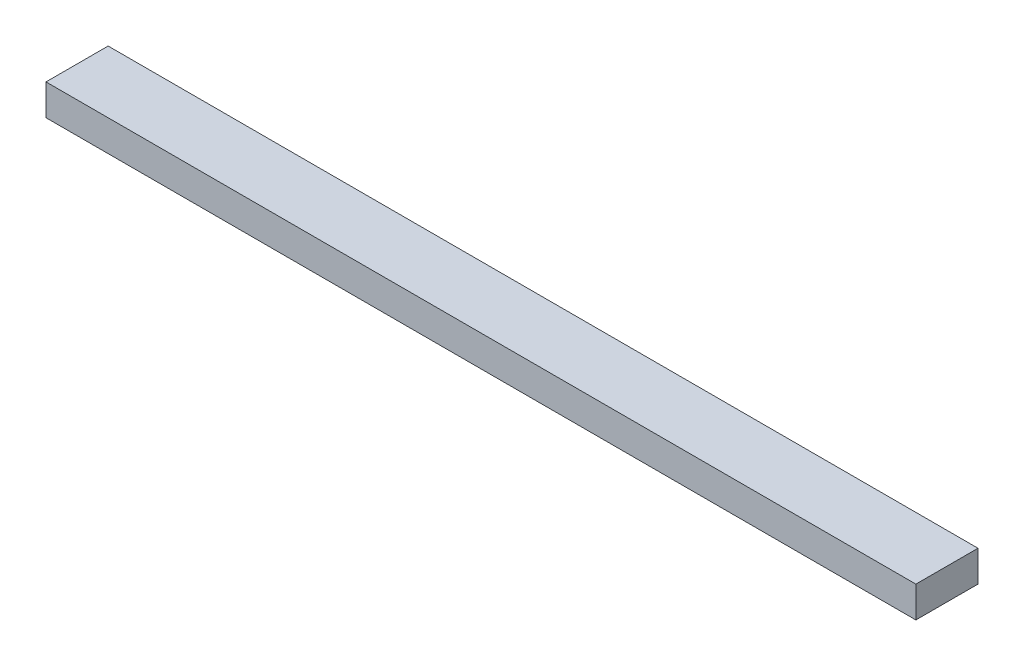
SolidWorks part; units mm, degrees
ref_plane "Front" through (0, 0, 0) normal (0, 0, 1) x (1, 0, 0)
ref_plane "Top" through (0, 0, 0) normal (0, 1, 0) x (1, 0, 0)
ref_plane "Right" through (0, 0, 0) normal (1, 0, 0) x (0, 0, -1)
sketch "Эскиз1" plane through (0, 0, 0) normal (1, 0, 0) x (0, 0, -1)
  line L1 (355.6218, 629.0719) -> (395.6218, 629.0719)
  line L2 (355.6218, 629.0719) -> (355.6218, 609.0719)
  line L3 (355.6218, 609.0719) -> (395.6218, 609.0719)
  line L4 (395.6218, 629.0719) -> (395.6218, 609.0719)
  dimension "D1" = 40
  dimension "D2" = 20
extrude "Бобышка-Вытянуть1" add sketch "Эскиз1" along normal blind 560
